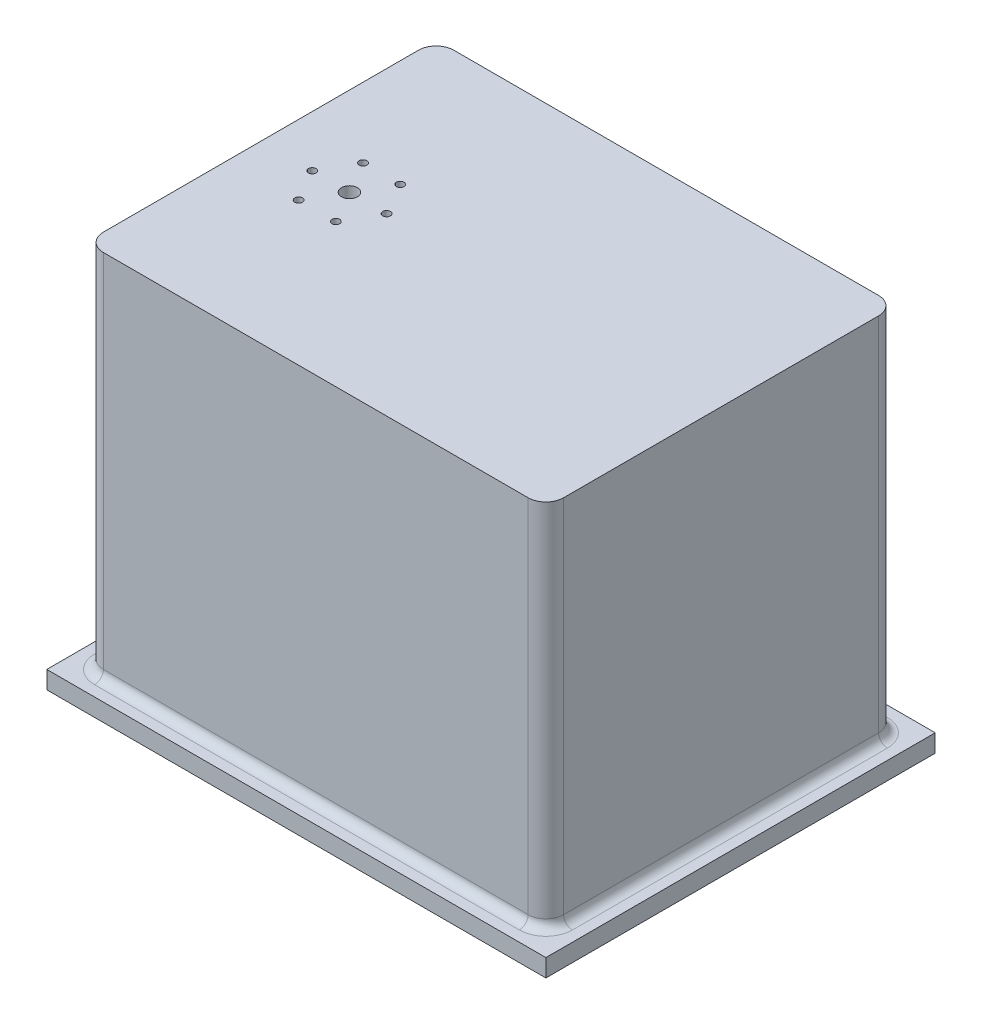
SolidWorks part; units mm, degrees
ref_plane "Front Plane" through (0, 0, 0) normal (0, 0, 1) x (1, 0, 0)
ref_plane "Top Plane" through (0, 0, 0) normal (0, 1, 0) x (1, 0, 0)
ref_plane "Right Plane" through (0, 0, 0) normal (1, 0, 0) x (0, 0, -1)
sketch "Sketch1" plane through (0, 0, 0) normal (0, 1, 0) x (1, 0, 0)
  line L0 (-130, 99) -> (130, -99) construction
  line L1 (-130, 99) -> (130, 99)
  line L2 (-130, 99) -> (-130, -99)
  line L3 (-130, -99) -> (130, -99)
  line L4 (130, 99) -> (130, -99)
  line L5 (130, 99) -> (-130, -99) construction
  point P4 (0, 0)
  dimension "D1" = 198
  dimension "D2" = 260
extrude "Boss-Extrude1" add sketch "Sketch1" along normal blind 219
sketch "Sketch2" plane through (0, 0, 0) normal (0, 1, 0) x (1, 0, 0)
  line L14 (-120, 89) -> (-120, -89)
  line L15 (120, 89) -> (-120, 89)
  line L16 (-120, -89) -> (120, -89)
  line L17 (120, -89) -> (120, 89)
  line L18 (-120, 89) -> (-120, -89)
  line L19 (120, 89) -> (-120, 89)
  line L20 (-120, -89) -> (120, -89)
  line L21 (120, -89) -> (120, 89)
  dimension "D1" = 10
extrude "Cut-Extrude1" cut sketch "Sketch2" along normal blind 209
sketch "Sketch3" plane through (0, 0, 0) normal (0, 1, 0) x (1, 0, 0)
  line L14 (141, 110) -> (-141, 110)
  line L15 (141, -110) -> (141, 110)
  line L16 (-141, 110) -> (-141, -110)
  line L17 (-141, -110) -> (141, -110)
  line L18 (141, 110) -> (-141, 110)
  line L19 (141, -110) -> (141, 110)
  line L20 (-141, 110) -> (-141, -110)
  line L21 (-141, -110) -> (141, -110)
  line L32 (130, -99) -> (130, 99)
  line L33 (130, 99) -> (-130, 99)
  line L34 (-130, 99) -> (-130, -99)
  line L35 (-130, -99) -> (130, -99)
  line L36 (130, -99) -> (130, 99)
  line L37 (130, 99) -> (-130, 99)
  line L38 (-130, 99) -> (-130, -99)
  line L39 (-130, -99) -> (130, -99)
  dimension "D1" = 11
  dimension "D2" = 0
extrude "Boss-Extrude2" add sketch "Sketch3" along normal blind 10
fillet "Fillet1" radius 10 4 edges at (-130, 114.5, -99) (-130, 114.5, 99) (130, 114.5, -99) (130, 114.5, 99)
fillet "Fillet3" radius 5 8 edges at (-127.0711, 10, 96.0711) (-130, 10, 0) (-127.0711, 10, -96.0711) (0, 10, -99) (127.0711, 10, -96.0711) (130, 10, 0) (127.0711, 10, 96.0711) (0, 10, 99)
sketch "Sketch4" plane through (0, 219, 0) normal (0, 1, 0) x (1, 0, 0)
  circle A0 centre (-80, 0) radius 21 construction
  circle A1 centre (-59, 0) radius 2.17
  circle A2 centre (-69.5, -18.1865) radius 2.17
  circle A3 centre (-90.5, -18.1865) radius 2.17
  circle A4 centre (-101, 0) radius 2.17
  circle A5 centre (-90.5, 18.1865) radius 2.17
  circle A6 centre (-69.5, 18.1865) radius 2.17
  circle A7 centre (-80, 0) radius 4.5
  point P18 (-80, 0)
  dimension "D1" = 42
  dimension "D3" = 4.34
  dimension "D5" = 9
  dimension "D2" = 80
  dimension "D4" = 6
extrude "Cut-Extrude3" cut sketch "Sketch4" against normal blind 20
